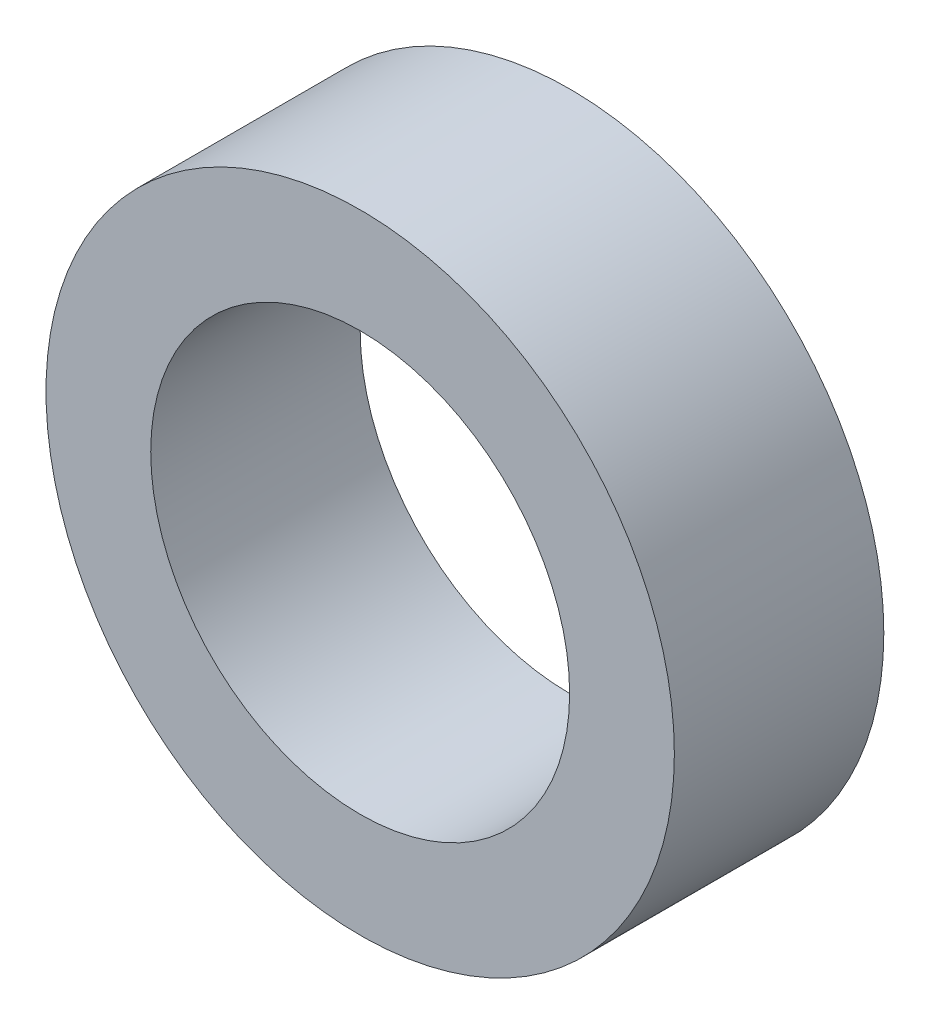
SolidWorks part; units mm, degrees
material "Plain Carbon Steel"
ref_plane "Front Plane" through (0, 0, 0) normal (0, 0, 1) x (1, 0, 0)
ref_plane "Top Plane" through (0, 0, 0) normal (0, 1, 0) x (1, 0, 0)
ref_plane "Right Plane" through (0, 0, 0) normal (1, 0, 0) x (0, 0, -1)
sketch "Sketch1" plane through (0, 0, 0) normal (0, 0, 1) x (1, 0, 0)
  circle A0 centre (0, 0) radius 3.175
  circle A1 centre (0, 0) radius 4.7625
  dimension "D1" = 6.35
  dimension "D2" = 9.525
extrude "Boss-Extrude1" add sketch "Sketch1" along normal blind 3.175
